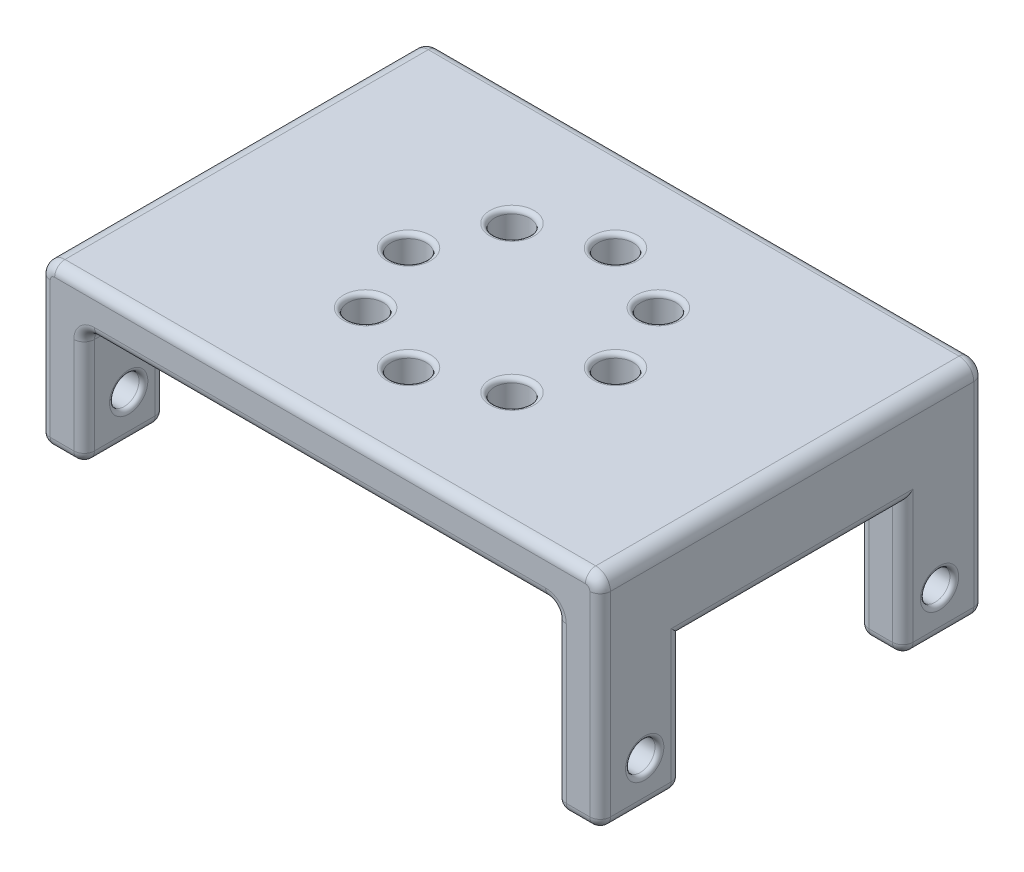
SolidWorks part; units mm, degrees
other "相机1"
ref_plane "Front Plane" through (0, 0, 0) normal (0, 0, 1) x (1, 0, 0)
ref_plane "Top Plane" through (0, 0, 0) normal (0, 1, 0) x (1, 0, 0)
ref_plane "Right Plane" through (0, 0, 0) normal (1, 0, 0) x (0, 0, -1)
sketch "Sketch1" plane through (0, 0, 0) normal (0, 1, 0) x (1, 0, 0)
  line L1 (-19, 12.02) -> (19, 12.02)
  line L2 (-19, 12.02) -> (-19, -12.02)
  line L3 (-19, -12.02) -> (19, -12.02)
  line L4 (19, 12.02) -> (19, -12.02)
  line L5 (-19, 12.02) -> (19, -12.02) construction
  line L6 (-19, -12.02) -> (19, 12.02) construction
  circle A0 centre (0, 7.02) radius 1.2
  circle A1 centre (4.9639, 4.9639) radius 1.2
  circle A2 centre (7.02, 0) radius 1.2
  circle A3 centre (4.9639, -4.9639) radius 1.2
  circle A4 centre (0, -7.02) radius 1.2
  circle A5 centre (-4.9639, -4.9639) radius 1.2
  circle A6 centre (-7.02, 0) radius 1.2
  circle A7 centre (-4.9639, 4.9639) radius 1.2
  point P0 (0, 0)
  point P24 (0, 0)
  dimension "D3" = 2.4
  dimension "D4" = 7.02
  dimension "D7" = 9.9278
  dimension "D1" = 38
  dimension "D2" = 24.04
  dimension "D5" = 8
  dimension "D6" = 7.0561
extrude "Boss-Extrude1" add sketch "Sketch1" along normal blind 3
sketch "Sketch2" plane through (19, 0, 0) normal (1, 0, 0) x (0, 0, -1)
  line L0 (12.02, 3) -> (12.02, 0) construction
  line L1 (12.02, 3) -> (12.02, 0)
  line L2 (7.5, -11.95) -> (12.02, -11.95)
  line L3 (-12.02, 0) -> (12.02, 0)
  line L4 (-12.02, 0) -> (-12.02, -11.95)
  line L5 (-12.02, -11.95) -> (-7.5, -11.95)
  line L6 (12.02, 0) -> (12.02, -11.95)
  line L7 (-7.5, -2.95) -> (7.5, -2.95)
  line L8 (-7.5, -2.95) -> (-7.5, -11.95)
  line L10 (7.5, -2.95) -> (7.5, -11.95)
  line L11 (0, 16.4113) -> (0, -19.9375) construction
  circle A0 centre (10, -8.95) radius 1
  circle A1 centre (-10, -8.95) radius 1
  point P5 (0, -11.95)
  line M10 (-12.02, 0) -> (12.02, 0)
  dimension "D4" = 2
  dimension "D1" = 11.95
  dimension "D2" = 9
  dimension "D3" = 15
  dimension "D5" = 2.5
  dimension "D6" = 7.5
  dimension "D7" = 3
extrude "Boss-Extrude2" add sketch "Sketch2" against normal blind 3 contours L11 L4 L5 L8 L7 A1 M10 | L3 L11 L7 L10 L2 L6 A0
sketch "Sketch3" plane through (-19, 0, 0) normal (-1, 0, 0) x (0, 0, 1)
  line L0 (12.02, 3) -> (12.02, 0) construction
  line L1 (12.02, 3) -> (12.02, 0)
  line L2 (7.5, -7.95) -> (12.02, -7.95)
  line L3 (-12.02, 0) -> (12.02, 0)
  line L4 (-12.02, 0) -> (-12.02, -7.95)
  line L5 (-12.02, -7.95) -> (-7.5, -7.95)
  line L6 (12.02, 0) -> (12.02, -7.95)
  line L7 (-7.5, -2.95) -> (7.5, -2.95)
  line L8 (-7.5, -2.95) -> (-7.5, -7.95)
  line L10 (7.5, -2.95) -> (7.5, -7.95)
  line L11 (0, 3.5412) -> (0, -14.6742) construction
  circle A0 centre (10, -4.95) radius 1
  circle A1 centre (-10, -4.95) radius 1
  point P5 (0, -9.26)
  line M12 (-12.02, 0) -> (12.02, 0)
  dimension "D4" = 2
  dimension "D1" = 7.95
  dimension "D2" = 15
  dimension "D3" = 5
  dimension "D5" = 2.5
  dimension "D6" = 7.5
  dimension "D7" = 3
extrude "Boss-Extrude3" add sketch "Sketch3" against normal blind 3 contours L11 L4 L5 L8 L7 A1 M12 | L3 L11 L7 L10 L2 L6 A0
sketch "草图1" plane through (0, 0, 12.02) normal (0, 0, 1) x (1, 0, 0)
  line L0 (-19, 3) -> (-19, -7.95)
  line L1 (-19, -7.95) -> (-16, -7.95)
  line L2 (-16, -7.95) -> (-16, 0)
  line L3 (-16, 0) -> (16, 0)
  line L4 (16, 0) -> (16, -11.95)
  line L5 (16, -11.95) -> (19, -11.95)
  line L6 (19, -11.95) -> (19, 3)
  line L7 (19, 3) -> (-19, 3)
extrude "凸台-拉伸1" add sketch "草图1" along normal blind 1
sketch "草图2" plane through (0, 0, -12.02) normal (0, 0, -1) x (-1, 0, 0)
  line L0 (-19, 3) -> (-19, -11.95)
  line L1 (-19, -11.95) -> (-16, -11.95)
  line L2 (-16, -11.95) -> (-16, 0)
  line L3 (-16, 0) -> (16, 0)
  line L4 (16, 0) -> (16, -7.95)
  line L5 (16, -7.95) -> (19, -7.95)
  line L6 (19, -7.95) -> (19, 3)
  line L7 (19, 3) -> (-19, 3)
extrude "凸台-拉伸2" add sketch "草图2" along normal blind 1
fillet "圆角1" radius 1 1 edges at (-19, 3, 0)
fillet "圆角2" radius 1 1 edges at (19, 3, 0)
fillet "圆角3" radius 0.7 46 edges at (16, 0, 0) (-16, 0, 0) (-17.5, -7.95, 7.5) (17.5, -11.95, -13.02) (-19, -7.95, 10.26) (-16, -7.95, 10.26) (19, -11.95, -10.26) (-17.5, -7.95, -13.02) (-16, -3.975, -13.02) (-19, -7.95, -10.26) (-16, -7.95, -10.26) (-19, -5.45, 7.5) (-16, -5.45, 7.5) (-19, -2.95, 0) (-16, -2.95, 0) (16, -5.975, -13.02) (0, 0, -13.02) (18.7071, 2.7071, -13.02) (19, -4.975, -13.02) (19, -2.95, 0) (16, -2.95, 0) (-17.5, -7.95, 13.02) (16, -11.95, -10.26) (17.5, -11.95, -7.5) (19, -7.45, -7.5) (16, -7.45, -7.5) (19, -11.95, 10.26) (16, -11.95, 10.26) (19, -7.45, 7.5) (16, -7.45, 7.5) (19, -4.975, 13.02) (18.7071, 2.7071, 13.02) (17.5, -11.95, 13.02) (16, -5.975, 13.02) (0, 0, 13.02) (0, 3, -13.02) (-19, -2.975, -13.02) (-18.7071, 2.7071, -13.02) (-17.5, -7.95, -7.5) (-19, -5.45, -7.5) (-16, -5.45, -7.5) (-16, -3.975, 13.02) (0, 3, 13.02) (-18.7071, 2.7071, 13.02) (-19, -2.975, 13.02) (17.5, -11.95, 7.5)
fillet "圆角4" radius 0.3 24 edges at (4.9639, 3, -3.7639) (4.9639, 0, -3.7639) (0, 3, -5.82) (0, 0, -5.82) (-4.9639, 3, -3.7639) (-4.9639, 0, -3.7639) (-7.02, 3, 1.2) (-7.02, 0, 1.2) (-4.9639, 3, 6.1639) (-4.9639, 0, 6.1639) (0, 3, 8.22) (0, 0, 8.22) (4.9639, 3, 6.1639) (4.9639, 0, 6.1639) (7.02, 3, 1.2) (7.02, 0, 1.2) (-19, -4.95, -9) (-19, -4.95, 11) (16, -8.95, -11) (19, -8.95, -11) (16, -8.95, 9) (19, -8.95, 9) (-16, -4.95, -9) (-16, -4.95, 11)
